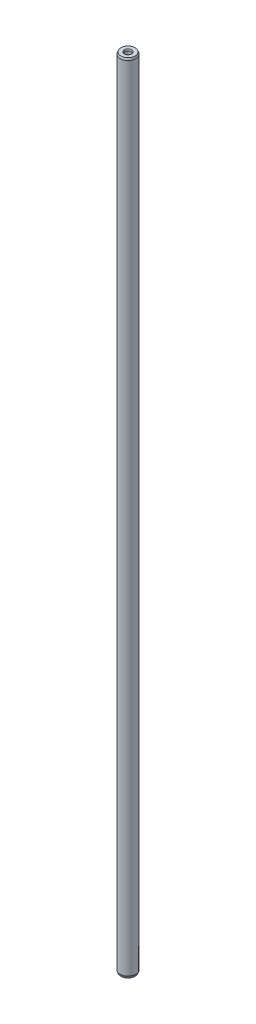
SolidWorks part; units mm, degrees
ref_plane "Front Plane" through (0, 0, 0) normal (0, 0, 1) x (1, 0, 0)
ref_plane "Top Plane" through (0, 0, 0) normal (0, 1, 0) x (1, 0, 0)
ref_plane "Right Plane" through (0, 0, 0) normal (1, 0, 0) x (0, 0, -1)
ref_plane "Plane1" through (0, 0, -1.1264) normal (0, 0, -1) x (-1, 0, 0)
sketch "Sketch1" plane through (0, 0, -1.1264) normal (0, 0, -1) x (-1, 0, 0)
  line L0 (-0.0644, -144.1991) -> (1.0659, -143.5199)
  line L1 (1.0659, -143.5199) -> (1.0659, 148.4918)
  line L2 (1.0659, 148.4918) -> (-0.0644, 149.1709)
  line L3 (-0.0644, 149.1709) -> (-0.0644, 154.446)
  line L4 (-0.0644, 154.446) -> (-0.3184, 154.8859)
  line L5 (-0.3184, 154.8859) -> (-1.6773, 154.8859)
  line L6 (-1.6773, 154.8859) -> (-1.9313, 154.1239)
  line L7 (-1.9313, 154.1239) -> (-1.9313, -149.1521)
  line L8 (-1.9313, -149.1521) -> (-1.6773, -149.9141)
  line L9 (-1.6773, -149.9141) -> (-0.3184, -149.9141)
  line L10 (-0.3184, -149.9141) -> (-0.0644, -149.4741)
  line L11 (-0.0644, -149.4741) -> (-0.0644, -144.1991)
  line L12 (1.0659, -149.9141) -> (1.0659, 154.8859) construction
revolve "Revolve1" add sketch "Sketch1" angle 360 about L12
